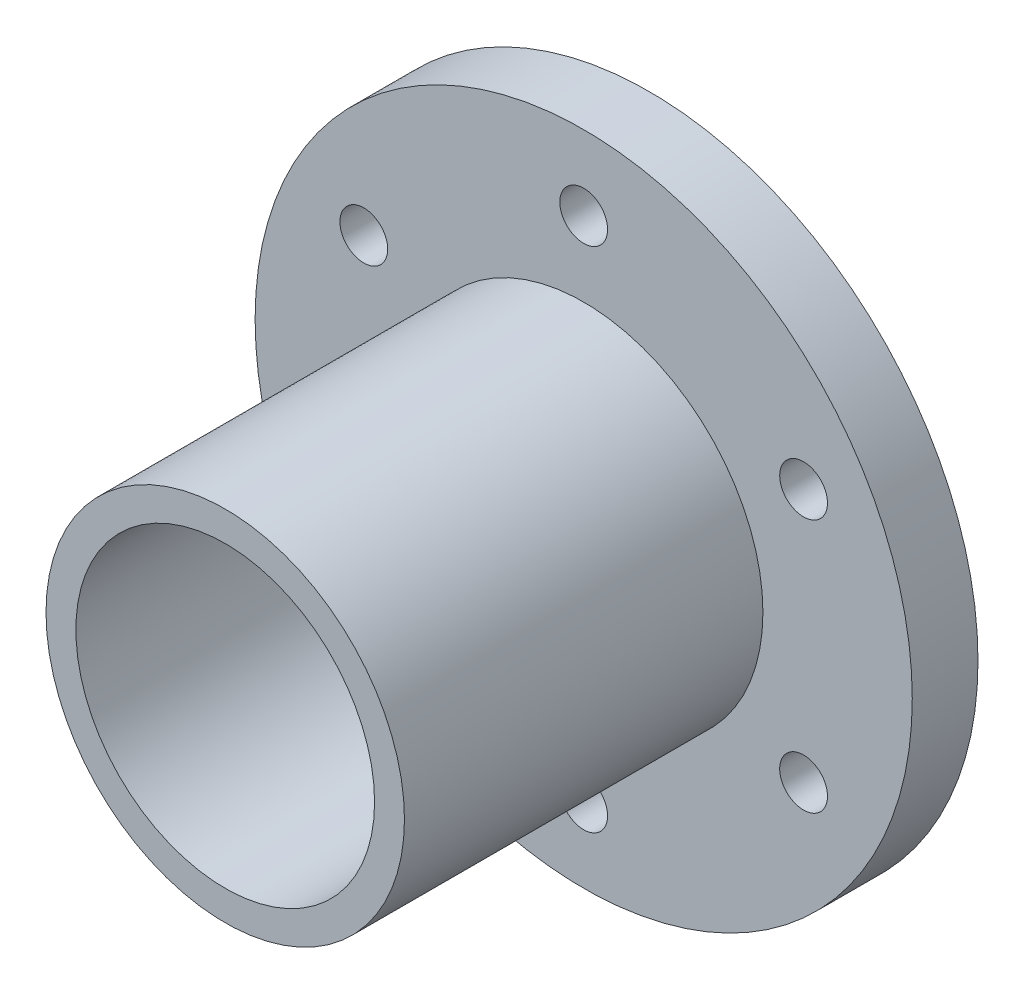
SolidWorks part; units mm, degrees
ref_plane "Front Plane" through (0, 0, 0) normal (0, 0, 1) x (1, 0, 0)
ref_plane "Top Plane" through (0, 0, 0) normal (0, 1, 0) x (1, 0, 0)
ref_plane "Right Plane" through (0, 0, 0) normal (1, 0, 0) x (0, 0, -1)
sketch "Sketch1" plane through (0, 0, 0) normal (0, 0, 1) x (1, 0, 0)
  circle A0 centre (0, 0) radius 110
  dimension "D1" = 220
extrude "Boss-Extrude2" add sketch "Sketch1" along normal blind 22
sketch "Sketch2" plane through (0, 0, 22) normal (0, 0, 1) x (1, 0, 0)
  circle A0 centre (0, 0) radius 60
  dimension "D1" = 120
extrude "Boss-Extrude3" add sketch "Sketch2" along normal blind 120
sketch "Sketch3" plane through (0, 0, 142) normal (0, 0, 1) x (1, 0, 0)
  circle A0 centre (0, 0) radius 50
  dimension "D1" = 100
extrude "Cut-Extrude1" cut sketch "Sketch3" against normal through all both and the other way through all
sketch "Sketch4" plane through (0, 0, 22) normal (0, 0, 1) x (1, 0, 0)
  line L0 (0, 0) -> (0, 85) construction
  circle A0 centre (0, 85) radius 8
  dimension "D2" = 16
  dimension "D1" = 85
extrude "Cut-Extrude2" cut sketch "Sketch4" against normal through all both
pattern_circular "CirPattern1" count 6 over 360 about axis through (0, 0, 0) along (0, 0, 1) of "Cut-Extrude2"
